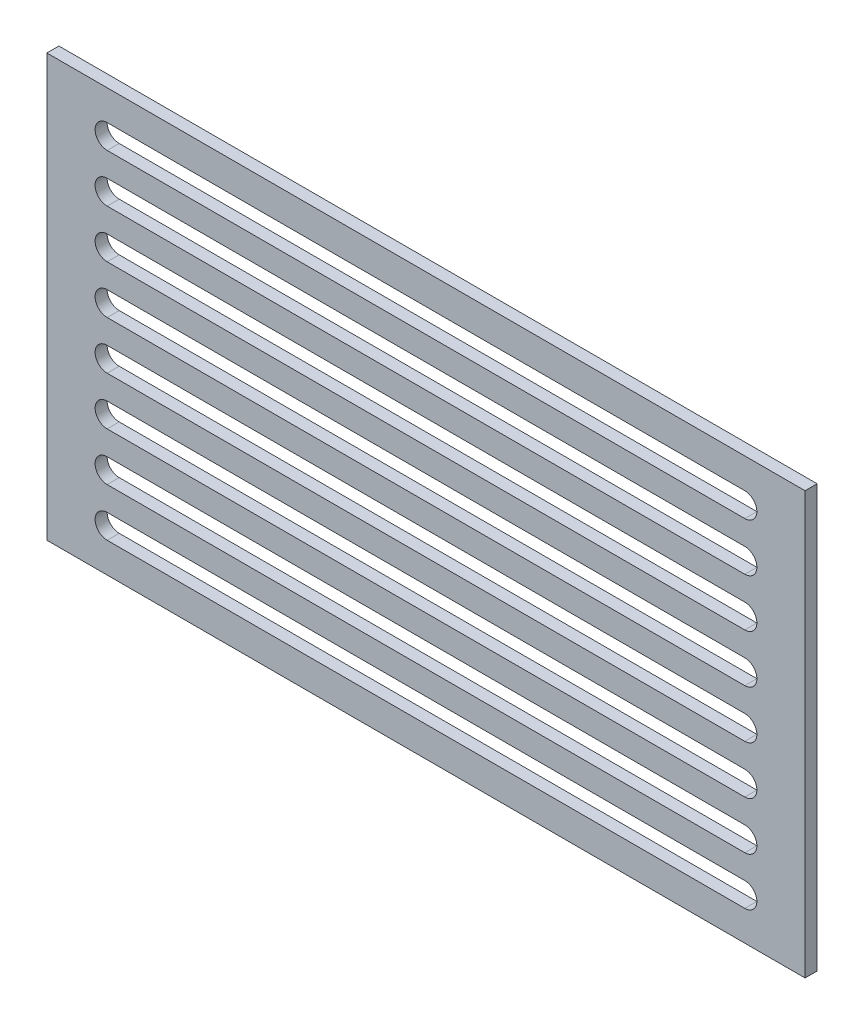
SolidWorks part; units mm, degrees
ref_plane "前视基准面" through (0, 0, 0) normal (0, 0, 1) x (1, 0, 0)
ref_plane "上视基准面" through (0, 0, 0) normal (0, 1, 0) x (1, 0, 0)
ref_plane "右视基准面" through (0, 0, 0) normal (1, 0, 0) x (0, 0, -1)
other "Configuration Table"
sketch "草图1" plane through (0, 0, 0) normal (0, 0, 1) x (1, 0, 0)
  line L0 (0, 7.6901) -> (0, -47.1033) construction
  line L1 (-62.885, -35) -> (62.885, -35)
  line L2 (-62.885, -35) -> (-62.885, 35)
  line L3 (-62.885, 35) -> (62.885, 35)
  line L4 (62.885, -35) -> (62.885, 35)
  line L5 (-62.885, -35) -> (62.885, 35) construction
  line L6 (-62.885, 35) -> (62.885, -35) construction
  line L7 (-81.5447, -20) -> (82.5882, -20) construction
  line L8 (-52.885, -20) -> (52.885, -20) construction
  line L13 (-52.885, -18) -> (52.885, -18)
  line L14 (-52.885, -22) -> (52.885, -22)
  line L17 (-52.885, -12) -> (52.885, -12) construction
  line L18 (-52.885, -10) -> (52.885, -10)
  line L19 (-52.885, -14) -> (52.885, -14)
  line L20 (-52.885, -4) -> (52.885, -4) construction
  line L21 (-52.885, -2) -> (52.885, -2)
  line L22 (-52.885, -6) -> (52.885, -6)
  line L23 (-52.885, 4) -> (52.885, 4) construction
  line L24 (-52.885, 6) -> (52.885, 6)
  line L25 (-52.885, 2) -> (52.885, 2)
  line L26 (-52.885, 12) -> (52.885, 12) construction
  line L27 (-52.885, 14) -> (52.885, 14)
  line L28 (-52.885, 10) -> (52.885, 10)
  line L29 (-52.885, 20) -> (52.885, 20) construction
  line L30 (-52.885, 22) -> (52.885, 22)
  line L31 (-52.885, 18) -> (52.885, 18)
  line L32 (-52.885, 28) -> (52.885, 28) construction
  line L33 (-52.885, 30) -> (52.885, 30)
  line L34 (-52.885, 26) -> (52.885, 26)
  line L35 (-52.885, -28) -> (52.885, -28) construction
  line L36 (-52.885, -26) -> (52.885, -26)
  line L37 (-52.885, -30) -> (52.885, -30)
  arc A3 (-52.885, -18) -> (-52.885, -22) centre (-52.885, -20) ccw
  arc A4 (52.885, -22) -> (52.885, -18) centre (52.885, -20) ccw
  arc A5 (-52.885, -10) -> (-52.885, -14) centre (-52.885, -12) ccw
  arc A6 (52.885, -14) -> (52.885, -10) centre (52.885, -12) ccw
  arc A7 (-52.885, -2) -> (-52.885, -6) centre (-52.885, -4) ccw
  arc A8 (52.885, -6) -> (52.885, -2) centre (52.885, -4) ccw
  arc A9 (-52.885, 6) -> (-52.885, 2) centre (-52.885, 4) ccw
  arc A10 (52.885, 2) -> (52.885, 6) centre (52.885, 4) ccw
  arc A11 (-52.885, 14) -> (-52.885, 10) centre (-52.885, 12) ccw
  arc A12 (52.885, 10) -> (52.885, 14) centre (52.885, 12) ccw
  arc A13 (-52.885, 22) -> (-52.885, 18) centre (-52.885, 20) ccw
  arc A14 (52.885, 18) -> (52.885, 22) centre (52.885, 20) ccw
  arc A15 (-52.885, 30) -> (-52.885, 26) centre (-52.885, 28) ccw
  arc A16 (52.885, 26) -> (52.885, 30) centre (52.885, 28) ccw
  arc A17 (-52.885, -26) -> (-52.885, -30) centre (-52.885, -28) ccw
  arc A18 (52.885, -30) -> (52.885, -26) centre (52.885, -28) ccw
  point P8 (0, 0)
  point P9 (0, -20)
  point P19 (0, -12)
  point P26 (0, -4)
  point P33 (0, 4)
  point P40 (0, 12)
  point P47 (0, 20)
  point P54 (0, 28)
  point P61 (0, -28)
  dimension "D4" = 4
  dimension "D7" = 2
  dimension "D1" = 125.77
  dimension "D2" = 70
  dimension "D3" = 10
  dimension "D5" = 15
  dimension "D6" = 7
extrude "凸台-拉伸1" add sketch "草图1" along normal blind 2
